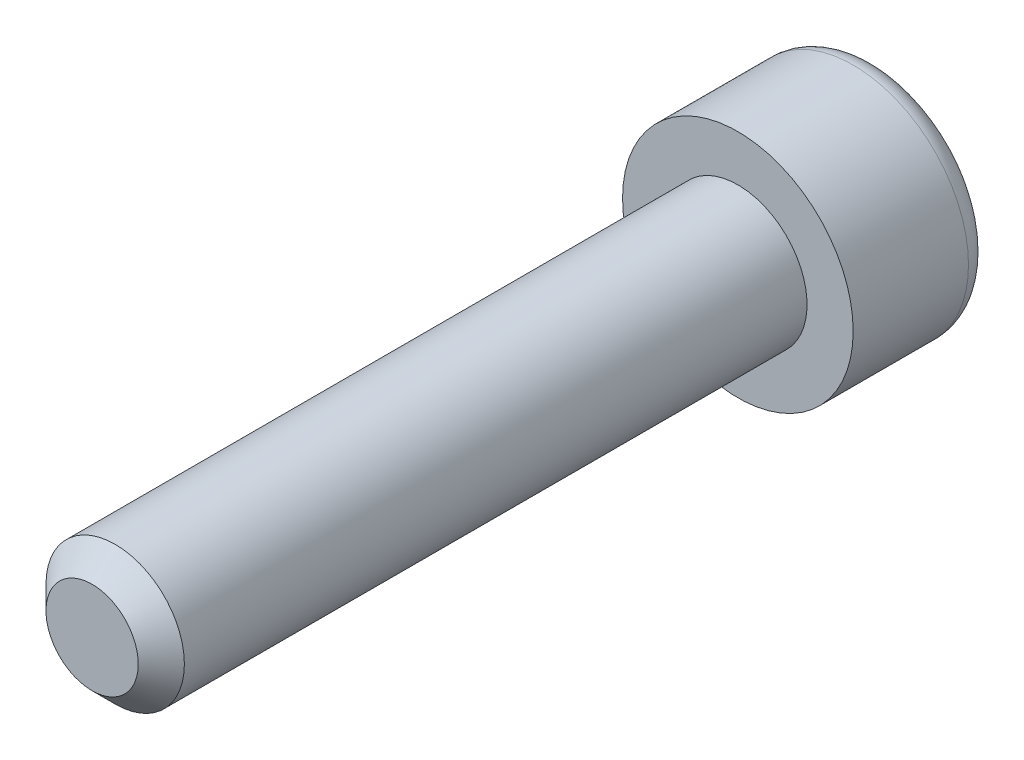
SolidWorks part; units mm, degrees
ref_plane "Face" through (0, 0, 0) normal (0, 0, 1) x (1, 0, 0)
ref_plane "Dessus" through (0, 0, 0) normal (0, 1, 0) x (1, 0, 0)
ref_plane "Droite" through (0, 0, 0) normal (1, 0, 0) x (0, 0, -1)
sketch "Esquisse1" plane through (0, 0, 0) normal (0, 0, 1) x (1, 0, 0)
  circle A0 centre (0, 0) radius 1.5
  dimension "D1" = 3
extrude "Base-Extrusion" add sketch "Esquisse1" along normal blind 14
chamfer "Chanfrein1" distance 0.5 angle 45 1 edges at (1.5, 0, 14)
sketch "Esquisse2" plane through (0, 0, 0) normal (0, 0, -1) x (-1, 0, 0)
  circle A0 centre (0, 0) radius 2.5
  dimension "D1" = 5
extrude "Boss.-Extru.1" add sketch "Esquisse2" along normal blind 3
fillet "Congé1" radius 0.5 1 edges at (-2.5, 0, -3)
sketch "Esquisse3" plane through (0, 0, -3) normal (0, 0, -1) x (-1, 0, 0)
  line L1 (1.7321, 0) -> (0.866, 1.5)
  line L2 (0.866, 1.5) -> (-0.866, 1.5)
  line L3 (-0.866, 1.5) -> (-1.7321, 0)
  line L4 (-1.7321, 0) -> (-0.866, -1.5)
  line L5 (-0.866, -1.5) -> (0.866, -1.5)
  line L6 (0.866, -1.5) -> (1.7321, 0)
  circle A0 centre (0, 0) radius 1.5 construction
  dimension "D1" = 3
extrude "Enlèv. mat.-Extru.1" cut sketch "Esquisse3" against normal blind 2.5
